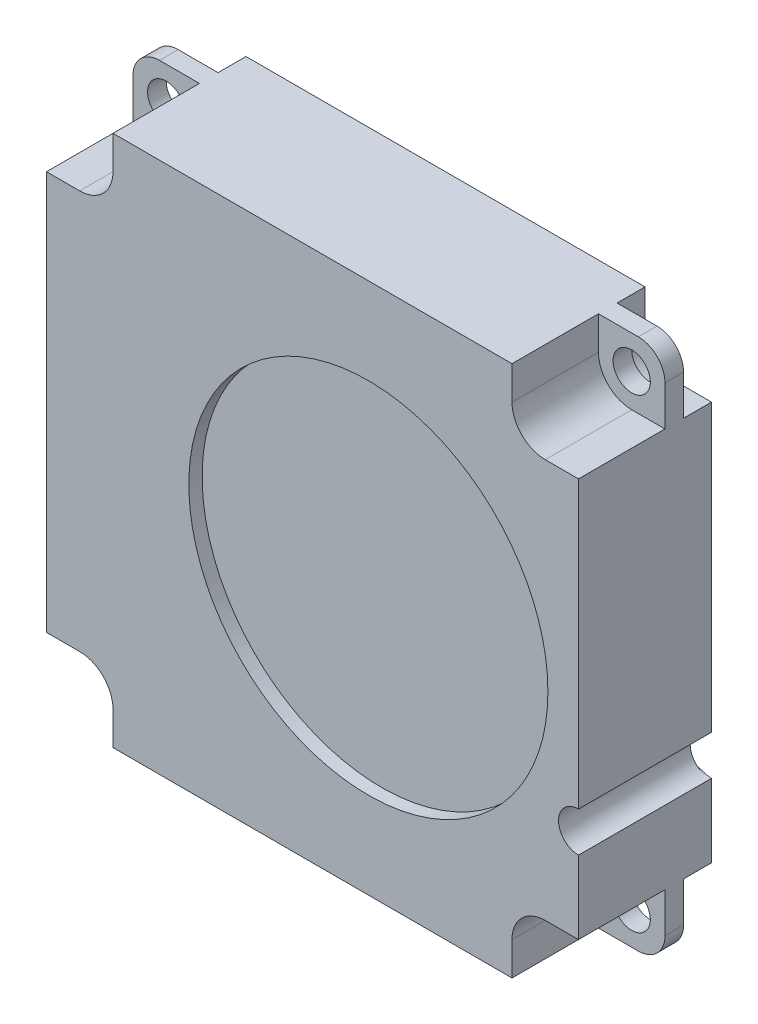
SolidWorks part; units mm, degrees
material "ABS"
ref_plane "Спереди" through (0, 0, 0) normal (0, 0, 1) x (1, 0, 0)
ref_plane "Сверху" through (0, 0, 0) normal (0, 1, 0) x (1, 0, 0)
ref_plane "Справа" through (0, 0, 0) normal (1, 0, 0) x (0, 0, -1)
other "Configuration Table"
sketch "Эскиз1" plane through (0, 0, 0) normal (0, 0, 1) x (1, 0, 0)
  line L1 (0, 0) -> (40, 0)
  line L2 (0, 0) -> (0, 40)
  line L3 (0, 40) -> (40, 40)
  line L4 (40, 0) -> (40, 40)
  dimension "D1" = 40
extrude "Бобышка-Вытянуть1" add sketch "Эскиз1" along normal blind 10
sketch "Эскиз2" plane through (0, 0, 10) normal (0, 0, 1) x (1, 0, 0)
  line L8 (2.5, 37.5) -> (2.5, 2.5)
  line L9 (2.5, 2.5) -> (37.5, 2.5)
  line L10 (37.5, 2.5) -> (37.5, 37.5)
  line L11 (37.5, 37.5) -> (2.5, 37.5)
  line L12 (2.5, 37.5) -> (2.5, 2.5) construction
  line L13 (2.5, 2.5) -> (37.5, 2.5) construction
  line L14 (37.5, 2.5) -> (37.5, 37.5) construction
  line L15 (37.5, 37.5) -> (2.5, 37.5) construction
  circle A0 centre (2.5, 37.5) radius 1.4
  circle A1 centre (37.5, 37.5) radius 1.4
  circle A2 centre (37.5, 2.5) radius 1.4
  circle A3 centre (2.5, 2.5) radius 1.4
  dimension "D2" = 2.8
  dimension "D1" = 2.5
extrude "Вырез-Вытянуть1" cut sketch "Эскиз2" against normal through all
sketch "Эскиз3" plane through (0, 0, 10) normal (0, 0, 1) x (1, 0, 0)
  line L0 (0, 0) -> (40, 0) construction
  line L1 (40, 0) -> (40, 40) construction
  circle A0 centre (24.2, 20) radius 13.5
  dimension "D1" = 27
  dimension "D2" = 20
  dimension "D3" = 15.8
extrude "Вырез-Вытянуть2" cut sketch "Эскиз3" against normal blind 1
sketch "Эскиз4" plane through (0, 0, 0) normal (0, -1, 0) x (1, 0, 0)
  line L0 (6, 9.3) -> (6, 0.7)
  line L1 (6, 0.7) -> (34, 0.7)
  line L2 (34, 0.7) -> (34, 9.3)
  line L3 (34, 9.3) -> (6, 9.3)
  line L4 (0, 10) -> (40, 10) construction
  line L5 (40, 10) -> (40, 0) construction
  point P6 (20, 10)
  point P7 (20, 9.3)
  point P10 (40, 5)
  point P11 (34, 5)
  dimension "D1" = 28
  dimension "D2" = 8.6
extrude "Вырез-Вытянуть3" cut sketch "Эскиз4" against normal blind 5
sketch "Эскиз5" plane through (0, 0, 10) normal (0, 0, 1) x (1, 0, 0)
  line L0 (2.5, 35) -> (0, 35)
  line L1 (0, 40) -> (0, 0) construction
  line L2 (0, 35) -> (0, 40)
  line L3 (0, 40) -> (5, 40)
  line L4 (40, 40) -> (0, 40) construction
  line L5 (5, 40) -> (5, 37.5)
  line L6 (20, 40) -> (20, 0) construction
  line L7 (0, 0) -> (40, 0) construction
  line L8 (0, 20) -> (40, 20) construction
  line L9 (40, 0) -> (40, 40) construction
  line L10 (35, 40) -> (35, 37.5)
  line L11 (40, 40) -> (35, 40)
  line L12 (40, 35) -> (40, 40)
  line L13 (37.5, 35) -> (40, 35)
  line L14 (37.5, 5) -> (40, 5)
  line L15 (40, 5) -> (40, 0)
  line L16 (40, 0) -> (35, 0)
  line L17 (35, 0) -> (35, 2.5)
  line L18 (5, 0) -> (5, 2.5)
  line L19 (0, 0) -> (5, 0)
  line L20 (0, 5) -> (0, 0)
  line L21 (2.5, 5) -> (0, 5)
  arc A0 (2.5, 35) -> (5, 37.5) centre (2.5, 37.5) ccw
  arc A1 (37.5, 35) -> (35, 37.5) centre (37.5, 37.5) cw
  arc A2 (37.5, 5) -> (35, 2.5) centre (37.5, 2.5) ccw
  arc A3 (2.5, 5) -> (5, 2.5) centre (2.5, 2.5) cw
extrude "Вырез-Вытянуть4" cut sketch "Эскиз5" against normal blind 6.5
sketch "Эскиз6" plane through (0, 0, 0) normal (0, 0, -1) x (-1, 0, 0)
  line L4 (-2.5, 35) -> (0, 35)
  line L5 (0, 35) -> (0, 40)
  line L6 (0, 40) -> (-5, 40)
  line L7 (-5, 40) -> (-5, 37.5)
  line L8 (-2.5, 35) -> (0, 35)
  line L9 (0, 35) -> (0, 40)
  line L10 (0, 40) -> (-5, 40)
  line L11 (-5, 40) -> (-5, 37.5)
  line L12 (-35, 37.5) -> (-35, 40)
  line L13 (-40, 35) -> (-37.5, 35)
  line L14 (-40, 40) -> (-40, 35)
  line L15 (-35, 40) -> (-40, 40)
  line L16 (-35, 37.5) -> (-35, 40)
  line L17 (-40, 35) -> (-37.5, 35)
  line L18 (-40, 40) -> (-40, 35)
  line L19 (-35, 40) -> (-40, 40)
  line L20 (-5, 0) -> (0, 0)
  line L21 (0, 0) -> (0, 5)
  line L22 (0, 5) -> (-2.5, 5)
  line L23 (-5, 2.5) -> (-5, 0)
  line L24 (-5, 0) -> (0, 0)
  line L25 (0, 0) -> (0, 5)
  line L26 (0, 5) -> (-2.5, 5)
  line L27 (-5, 2.5) -> (-5, 0)
  line L28 (-40, 5) -> (-40, 0)
  line L29 (-40, 0) -> (-35, 0)
  line L30 (-35, 0) -> (-35, 2.5)
  line L31 (-37.5, 5) -> (-40, 5)
  line L32 (-40, 5) -> (-40, 0)
  line L33 (-40, 0) -> (-35, 0)
  line L34 (-35, 0) -> (-35, 2.5)
  line L35 (-37.5, 5) -> (-40, 5)
  arc A1 (-5, 37.5) -> (-2.5, 35) centre (-2.5, 37.5) ccw
  arc A2 (-5, 37.5) -> (-2.5, 35) centre (-2.5, 37.5) ccw
  arc A3 (-37.5, 35) -> (-35, 37.5) centre (-37.5, 37.5) ccw
  arc A4 (-37.5, 35) -> (-35, 37.5) centre (-37.5, 37.5) ccw
  arc A5 (-2.5, 5) -> (-5, 2.5) centre (-2.5, 2.5) ccw
  arc A6 (-2.5, 5) -> (-5, 2.5) centre (-2.5, 2.5) ccw
  arc A7 (-35, 2.5) -> (-37.5, 5) centre (-37.5, 2.5) ccw
  arc A8 (-35, 2.5) -> (-37.5, 5) centre (-37.5, 2.5) ccw
  dimension "D1" = 0
  dimension "D2" = 0
  dimension "D3" = 0
  dimension "D4" = 0
extrude "Вырез-Вытянуть5" cut sketch "Эскиз6" against normal blind 2.1
fillet "Скругление2" radius 2 4 edges at (40, 0, 2.8) (0, 0, 2.8) (40, 40, 2.8) (0, 40, 2.8)
sketch "Эскиз8" plane through (0, 0, 10) normal (0, 0, 1) x (1, 0, 0)
  line L0 (40, 5) -> (40, 35) construction
  line L1 (5, 0) -> (35, 0) construction
  circle A0 centre (40, 12) radius 1.5
  dimension "D2" = 3
  dimension "D1" = 12
extrude "Вырез-Вытянуть6" cut sketch "Эскиз8" against normal through all
sketch "Эскиз9" plane through (0, 0, 0) normal (0, 0, -1) x (-1, 0, 0)
  line L0 (-35, 40) -> (-5, 40) construction
  line L1 (0, 35) -> (0, 5) construction
  line L2 (-40, 13.5) -> (-33.3145, 15.6728)
  line L4 (-39.5364, 10.5734) -> (-32.1158, 12.9851)
  arc A0 (-32.1158, 12.9851) -> (-33.3145, 15.6728) centre (-20, 20) ccw
  arc A1 (-40, 10.5) -> (-40, 13.5) centre (-40, 12) ccw construction
  arc A2 (-39.5364, 10.5734) -> (-40, 13.5) centre (-40, 12) ccw
  point P4 (-20, 40)
  point P7 (0, 20)
  dimension "D1" = 28
extrude "Вырез-Вытянуть7" cut sketch "Эскиз9" against normal blind 0.1
